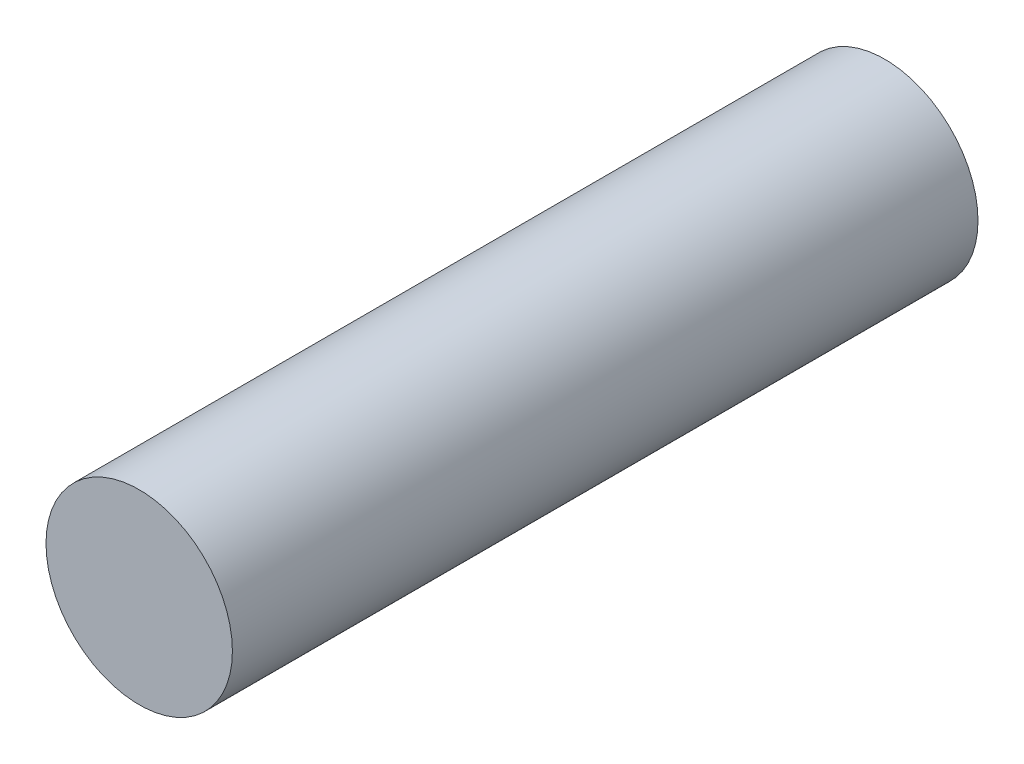
SolidWorks part; units mm, degrees
ref_plane "Front Plane" through (0, 0, 0) normal (0, 0, 1) x (1, 0, 0)
ref_plane "Top Plane" through (0, 0, 0) normal (0, 1, 0) x (1, 0, 0)
ref_plane "Right Plane" through (0, 0, 0) normal (1, 0, 0) x (0, 0, -1)
sketch "Sketch1" plane through (0, 0, 0) normal (0, 0, 1) x (1, 0, 0)
  circle A0 centre (0, 0) radius 3.175
  dimension "D1" = 6.35
extrude "Boss-Extrude1" add sketch "Sketch1" along normal blind 25.4
equation "\"Tout\"= 1.25"
equation "\"D\"= .25"
equation "\"shear stress\"= ( 5.1 * 1.25 ) / .015625"
equation "\"L\"= 1"
equation "\"D1@Sketch1\"=\"D\""
equation "\"D1@Boss-Extrude1\"=\"L\""
